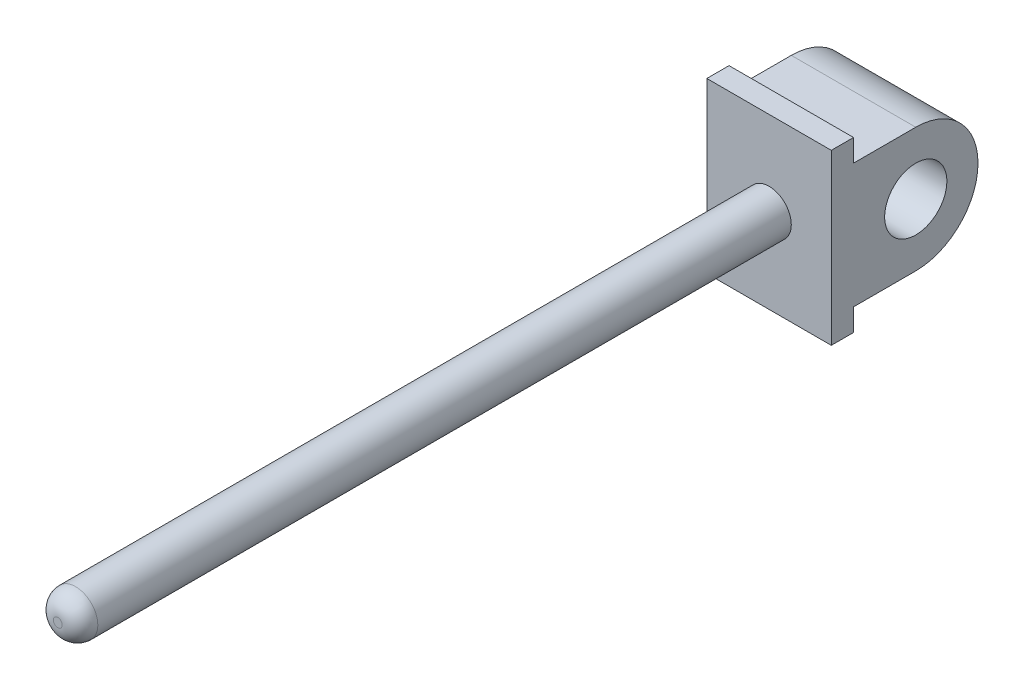
SolidWorks part; units mm, degrees
ref_plane "Front Plane" through (0, 0, 0) normal (0, 0, 1) x (1, 0, 0)
ref_plane "Top Plane" through (0, 0, 0) normal (0, 1, 0) x (1, 0, 0)
ref_plane "Right Plane" through (0, 0, 0) normal (1, 0, 0) x (0, 0, -1)
sketch "Sketch1" plane through (0, 0, 0) normal (1, 0, 0) x (0, 0, -1)
  line L3 (350, 0) -> (332.5, 0) construction
  line L5 (315, 35) -> (315, 47.5)
  line L6 (315, 47.5) -> (302.5, 47.5)
  line L8 (315, -35) -> (315, -47.5)
  line L9 (315, -47.5) -> (302.5, -47.5)
  line L10 (302.5, -47.5) -> (302.5, 47.5)
  line L11 (315, 35) -> (350, 35)
  line L12 (315, -35) -> (350, -35)
  arc A1 (350, -35) -> (350, 35) centre (350, 0) ccw
  circle A2 centre (350, 0) radius 17.5
  point P3 (175, 0)
  dimension "D1" = 35
  dimension "D7" = 35
  dimension "D2" = 70
  dimension "D5" = 12.5
  dimension "D8" = 12.5
  dimension "D9" = 35
extrude "Boss-Extrude2" add sketch "Sketch1" along normal blind 70 contours L11 A1 L12 L8 L9 L10 L6 L5
sketch "Sketch2" plane through (70, 0, 0) normal (1, 0, 0) x (0, 0, -1)
  line L0 (385, 0) -> (350, 0) construction
  line L1 (350, 0) -> (350, 35) construction
  arc A0 (350, -35) -> (350, 35) centre (350, 0) ccw construction
  circle A1 centre (350, 0) radius 17.5
  dimension "D1" = 35
extrude "Cut-Extrude1" cut sketch "Sketch2" against normal up to surface (70 mm away) up to face at (0, 0, -325)
ref_plane "Plane3" through (0, 0, -302.5) normal (0, 0, 1) x (1, 0, 0)
sketch "Sketch5" plane through (0, 0, -302.5) normal (0, 0, 1) x (1, 0, 0)
  line L0 (35, 47.5) -> (35, -47.5) construction
  line L1 (70, 47.5) -> (0, 47.5) construction
  line L2 (70, -47.5) -> (0, -47.5) construction
  line L3 (0, 0) -> (70, 0) construction
  line L4 (70, -47.5) -> (70, 47.5) construction
  circle A0 centre (35, 0) radius 12.5
  dimension "D1" = 25
extrude "Boss-Extrude3" add sketch "Sketch5" along normal blind 400
fillet "Fillet3" radius 10 1 edges at (47.5, 0, 97.5)
